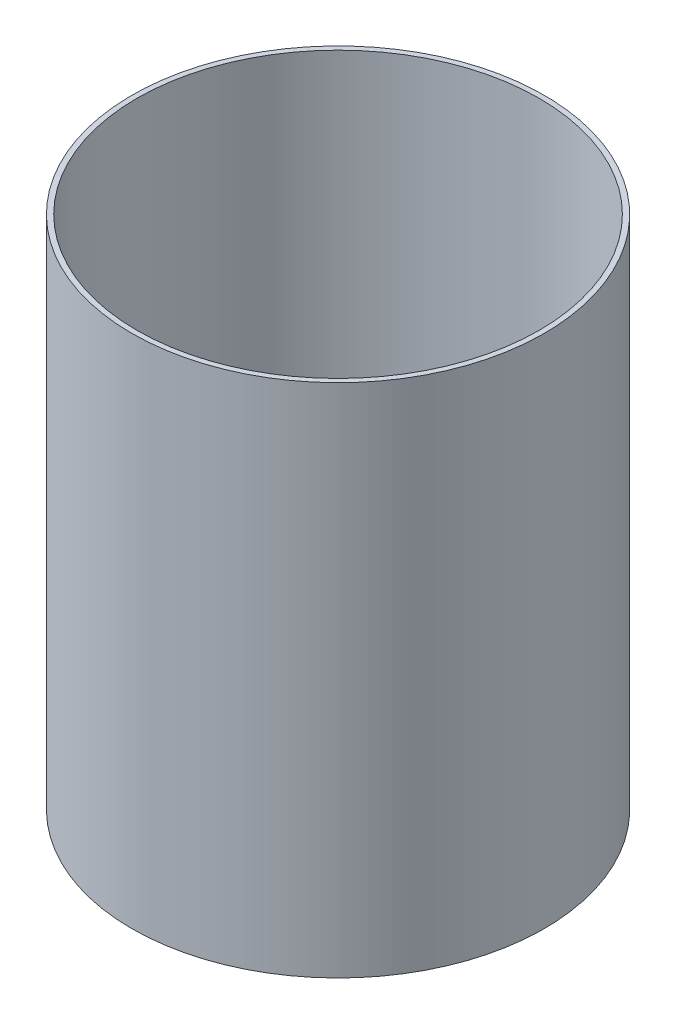
SolidWorks part; units mm, degrees
material "Hexcel AS4C (3000 Filaments)"
ref_plane "Front Plane" through (0, 0, 0) normal (0, 0, 1) x (1, 0, 0)
ref_plane "Top Plane" through (0, 0, 0) normal (0, 1, 0) x (1, 0, 0)
ref_plane "Right Plane" through (0, 0, 0) normal (1, 0, 0) x (0, 0, -1)
sketch "Sketch1" plane through (0, 0, 0) normal (0, 1, 0) x (1, 0, 0)
  circle A0 centre (0, 0) radius 101.6
  circle A1 centre (0, 0) radius 99.06
extrude "Boss-Extrude1" add sketch "Sketch1" along normal blind 254
